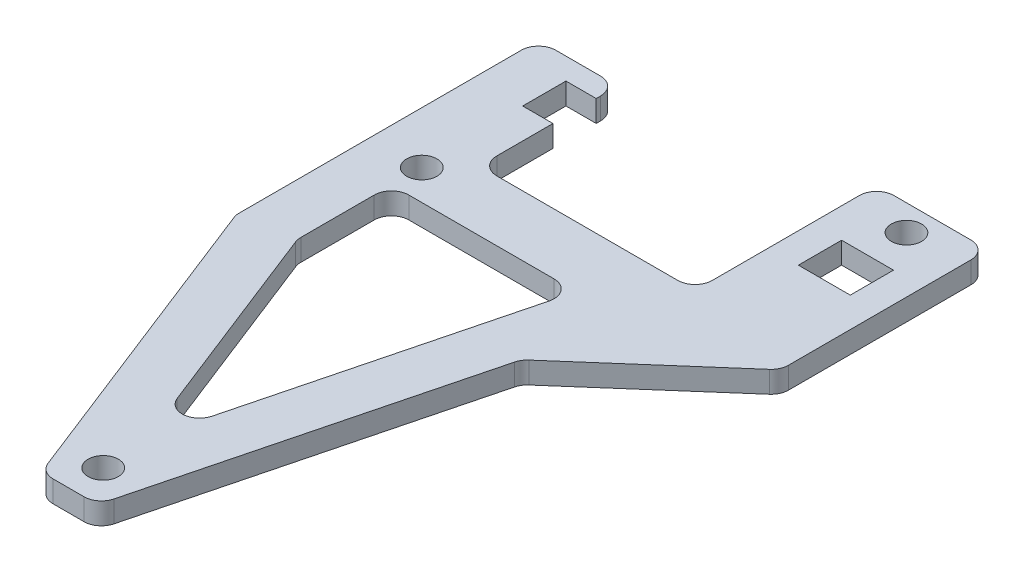
SolidWorks part; units mm, degrees
material "Thornel Mat VMA"
ref_plane "Front Plane" through (0, 0, 0) normal (0, 0, 1) x (1, 0, 0)
ref_plane "Top Plane" through (0, 0, 0) normal (0, 1, 0) x (1, 0, 0)
ref_plane "Right Plane" through (0, 0, 0) normal (1, 0, 0) x (0, 0, -1)
sketch "Sketch1" plane through (0, 0, 0) normal (0, 1, 0) x (1, 0, 0)
  line L0 (-15.635, 12) -> (5.735, 12)
  line L1 (5.735, 12) -> (-4.4013, -27.5316)
  line L2 (-4.4013, -27.5316) -> (-15.635, 1.1337)
  line L3 (-15.635, 1.1337) -> (-15.635, 12)
  line L4 (-21.635, 0) -> (-21.635, 35)
  line L5 (-21.635, 35) -> (-12.465, 35)
  line L6 (-12.465, 35) -> (-12.465, 19)
  line L7 (-12.465, 19) -> (12.465, 19)
  line L8 (12.465, 19) -> (12.465, 40)
  line L9 (12.465, 40) -> (25.365, 40)
  line L11 (25.365, 40) -> (25.365, 16)
  line L13 (-0.635, -37) -> (-7.135, -37)
  line L14 (-7.135, -37) -> (-21.635, 0)
  line L15 (25.365, 16) -> (9.365, 2)
  line L16 (9.365, 2) -> (-0.635, -37)
  point P12 (23.7131, 9.3436)
  point P15 (31.6935, 24.401)
  point P16 (23.2614, 14.3126)
  point P18 (11.9684, 23.4976)
  point P21 (0, 0)
  point P23 (8.9764, 1.1337)
  dimension "D1" = 6.5
  dimension "D2" = 6
  dimension "D3" = 6
  dimension "D4" = 24
  dimension "D5" = 6
  dimension "D6" = 39
  dimension "D7" = 7
  dimension "D8" = 21
  dimension "D9" = 12.9
  dimension "D10" = 16
  dimension "D11" = 9.17
  dimension "D12" = 47
  dimension "D13" = 56
  dimension "D14" = 37
  dimension "D15" = 14.5
  dimension "D16" = 12.465
  dimension "D17" = 31
extrude "Boss-Extrude1" add sketch "Sketch1" along normal mid plane 2.5
fillet "Fillet2" radius 2 15 edges at (-21.635, 0, 0) (-7.135, 0, 37) (-0.635, 0, 37) (9.365, 0, -2) (25.365, 0, -16) (25.365, 0, -40) (12.465, 0, -40) (12.465, 0, -19) (-12.465, 0, -19) (-12.465, 0, -35) (-21.635, 0, -35) (-4.4013, 0, 27.5316) (5.735, 0, -12) (-15.635, 0, -1.1337) (-15.635, 0, -12)
sketch "Sketch2" plane through (0, 1.25, 0) normal (0, 1, 0) x (1, 0, 0)
  line L0 (23.365, 40) -> (14.465, 40) construction
  line L4 (15.915, 32.5) -> (21.915, 32.5)
  line L5 (15.915, 32.5) -> (15.915, 27.5)
  line L6 (15.915, 27.5) -> (21.915, 27.5)
  line L7 (21.915, 32.5) -> (21.915, 27.5)
  line L8 (-12.465, 21) -> (-12.465, 33) construction
  line L9 (-12.465, 32.5) -> (-15.965, 32.5)
  line L10 (-12.465, 32.5) -> (-12.465, 27.5)
  line L11 (-12.465, 27.5) -> (-15.965, 27.5)
  line L12 (-15.965, 32.5) -> (-15.965, 27.5)
  line L13 (-21.635, 33) -> (-21.635, 0.3779) construction
  line L14 (3.1575, 12) -> (-13.635, 12) construction
  line L15 (-5.7707, -37) -> (-2.1869, -37) construction
  circle A0 centre (18.915, 37) radius 1.75
  circle A1 centre (-15.635, 15.5) radius 1.75
  circle A2 centre (-3.9788, -33) radius 1.75
  point P4 (18.915, 40)
  point P6 (18.915, 32.5)
  point P27 (-3.9788, -37)
  dimension "D1" = 3.5
  dimension "D8" = 6
  dimension "D9" = 3.5
  dimension "D10" = 4
  dimension "D2" = 3
  dimension "D3" = 5
  dimension "D4" = 5
  dimension "D5" = 6
  dimension "D6" = 7.5
  dimension "D7" = 3.5
extrude "Cut-Extrude1" cut sketch "Sketch2" against normal through all
